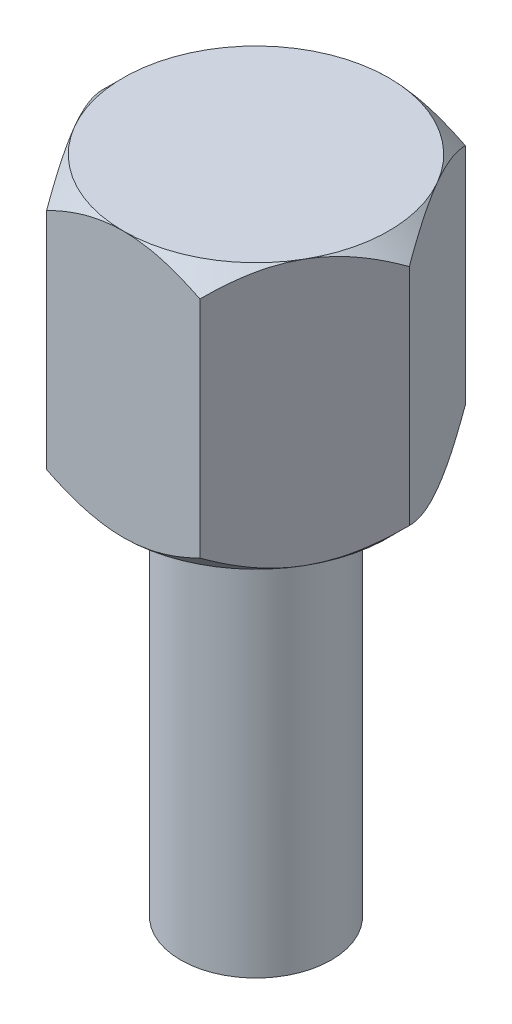
SolidWorks part; units mm, degrees
ref_plane "Front Plane" through (0, 0, 0) normal (0, 0, 1) x (1, 0, 0)
ref_plane "Top Plane" through (0, 0, 0) normal (0, 1, 0) x (1, 0, 0)
ref_plane "Right Plane" through (0, 0, 0) normal (1, 0, 0) x (0, 0, -1)
sketch "Sketch1" plane through (0, 0, 0) normal (0, 1, 0) x (1, 0, 0)
  line L1 (2.713, 0) -> (1.3565, 2.3495)
  line L2 (1.3565, 2.3495) -> (-1.3565, 2.3495)
  line L3 (-1.3565, 2.3495) -> (-2.713, 0)
  line L4 (-2.713, 0) -> (-1.3565, -2.3495)
  line L5 (-1.3565, -2.3495) -> (1.3565, -2.3495)
  line L6 (1.3565, -2.3495) -> (2.713, 0)
  circle A0 centre (0, 0) radius 2.3495 construction
  dimension "D1" = 4.699
extrude "Boss-Extrude1" add sketch "Sketch1" along normal blind 4.699
sketch "Sketch2" plane through (0, 0, 0) normal (0, -1, 0) x (1, 0, 0)
  circle A0 centre (0, 0) radius 1.3335
  dimension "D1" = 2.667
extrude "Boss-Extrude2" add sketch "Sketch2" along normal blind 6.985
sketch "Sketch3" plane through (0, 4.699, 0) normal (0, 1, 0) x (1, 0, 0)
  circle A0 centre (0, 0) radius 2.3495
sketch "Sketch5" plane through (0, 0, 0) normal (1, 0, 0) x (0, 0, -1)
  line L0 (2.3495, 4.699) -> (-2.3495, 4.699) construction
  line L1 (2.3495, 4.699) -> (-2.3495, 4.699) construction
  line L2 (2.3495, 4.699) -> (3.2232, 3.8253)
  line L3 (2.3495, 4.699) -> (3.2232, 4.699)
  line L4 (3.2232, 4.699) -> (3.2232, 3.8253)
  line L5 (0, 4.699) -> (0, 6.2255) construction
  dimension "D1" = 45
revolve "Cut-Revolve1" cut sketch "Sketch5" angle 360 about L5
ref_point "Point1"
ref_plane "Plane1" through (0, 2.3495, 0) normal (0, 1, 0) x (1, 0, 0)
mirror "Mirror1" about plane through (0, 2.3495, 0) normal (0, 1, 0) of "Cut-Revolve1"
